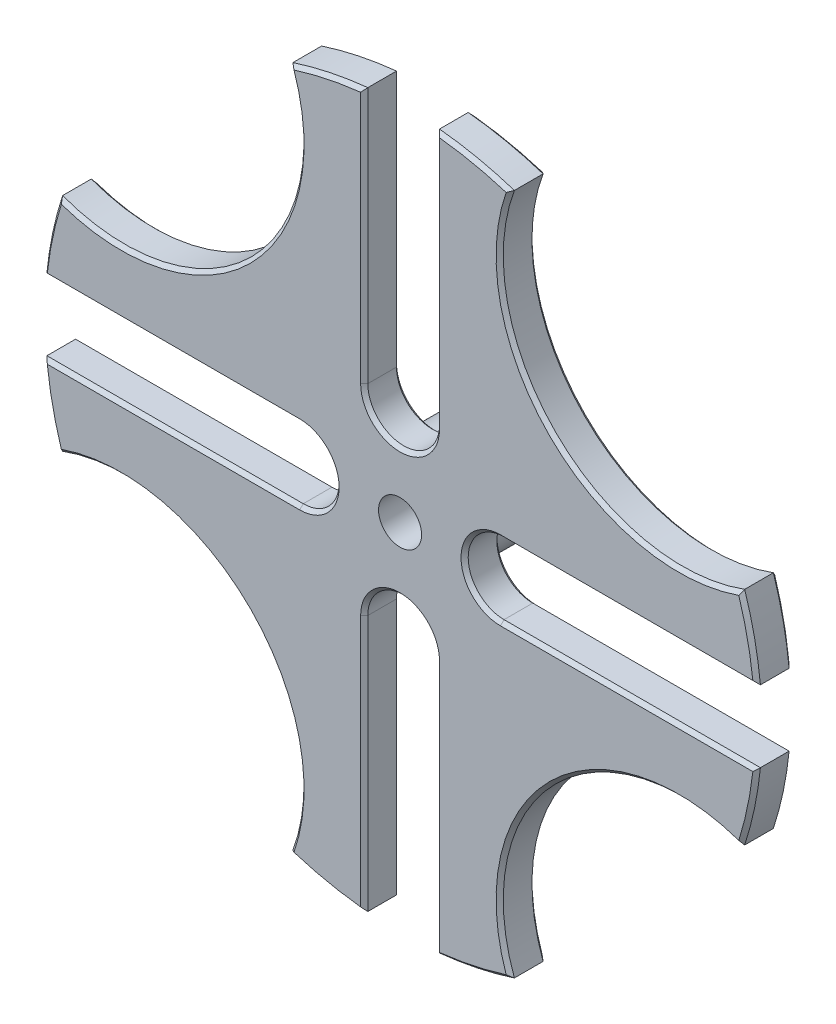
SolidWorks part; units mm, degrees
ref_plane "Ön Düzlem" through (0, 0, 0) normal (0, 0, 1) x (1, 0, 0)
ref_plane "Üst Düzlem" through (0, 0, 0) normal (0, 1, 0) x (1, 0, 0)
ref_plane "Sağ Düzlem" through (0, 0, 0) normal (1, 0, 0) x (0, 0, -1)
sketch "Sketch1" plane through (0, 0, 0) normal (0, 0, 1) x (1, 0, 0)
  circle A0 centre (0, 0) radius 50
  circle A1 centre (0, 0) radius 3
  dimension "D1" = 100
  dimension "D2" = 6
extrude "Boss-Extrude1" add sketch "Sketch1" along normal blind 5
sketch "Sketch2" plane through (0, 0, 5) normal (0, 0, 1) x (1, 0, 0)
  line L0 (0, 79.311) -> (0, -63.2271) construction
  line L1 (-72.315, 0) -> (65.8808, 0) construction
  line L2 (0, 14) -> (0, 86) construction
  line L3 (-5, 14) -> (-5, 86)
  line L4 (5, 14) -> (5, 86)
  line L5 (14, 0) -> (86, 0) construction
  line L6 (14, 5) -> (86, 5)
  line L7 (14, -5) -> (86, -5)
  line L8 (0, -14) -> (0, -86) construction
  line L9 (5, -14) -> (5, -86)
  line L10 (-5, -14) -> (-5, -86)
  line L11 (-14, 0) -> (-86, 0) construction
  line L12 (-14, -5) -> (-86, -5)
  line L13 (-14, 5) -> (-86, 5)
  line L14 (0, 0) -> (38.8909, 38.8909) construction
  arc A0 (-5, 14) -> (5, 14) centre (0, 14) ccw
  arc A1 (5, 86) -> (-5, 86) centre (0, 86) ccw
  circle A2 centre (0, 0) radius 50 construction
  arc A3 (14, 5) -> (14, -5) centre (14, 0) ccw
  arc A4 (86, -5) -> (86, 5) centre (86, 0) ccw
  arc A5 (5, -14) -> (-5, -14) centre (0, -14) ccw
  arc A6 (-5, -86) -> (5, -86) centre (0, -86) ccw
  arc A7 (-14, -5) -> (-14, 5) centre (-14, 0) ccw
  arc A8 (-86, 5) -> (-86, -5) centre (-86, 0) ccw
  circle A9 centre (38.8909, 38.8909) radius 25
  circle A10 centre (38.8909, -38.8909) radius 25
  circle A11 centre (-38.8909, -38.8909) radius 25
  circle A12 centre (-38.8909, 38.8909) radius 25
  point P7 (0, 50)
  point P19 (50, 0)
  point P26 (0, -50)
  point P33 (-50, 0)
  point P38 (0, 0)
  point P48 (0, 0)
  dimension "D1" = 5
  dimension "D6" = 50
  dimension "D2" = 72
  dimension "D4" = 45
  dimension "D5" = 55
  dimension "D3" = 4
  dimension "D7" = 4
extrude "Cut-Extrude1" cut sketch "Sketch2" against normal through all
chamfer "Chamfer1" distance 0.5 angle 45 50 edges at (3, 0, 0) (-21.2132, -21.2132, 0) (-10.279, -48.932, 0) (-5, -31.8747, 0) (0, -9, 0) (5, -31.8747, 0) (10.279, -48.932, 0) (21.2132, -21.2132, 0) (48.932, -10.279, 0) (31.8747, -5, 0) (9, 0, 0) (31.8747, 5, 0) (48.932, 10.279, 0) (21.2132, 21.2132, 0) (10.279, 48.932, 0) (5, 31.8747, 0) (0, 9, 0) (-5, 31.8747, 0) (-10.279, 48.932, 0) (-21.2132, 21.2132, 0) (-48.932, 10.279, 0) (-31.8747, 5, 0) (-9, 0, 0) (-31.8747, -5, 0) (-48.932, -10.279, 0) (3, 0, 5) (-9, 0, 5) (-31.8747, 5, 5) (-48.932, 10.279, 5) (-21.2132, 21.2132, 5) (-10.279, 48.932, 5) (-5, 31.8747, 5) (0, 9, 5) (5, 31.8747, 5) (10.279, 48.932, 5) (21.2132, 21.2132, 5) (48.932, 10.279, 5) (31.8747, 5, 5) (9, 0, 5) (31.8747, -5, 5) (48.932, -10.279, 5) (21.2132, -21.2132, 5) (10.279, -48.932, 5) (5, -31.8747, 5) (0, -9, 5) (-5, -31.8747, 5) (-10.279, -48.932, 5) (-21.2132, -21.2132, 5) (-48.932, -10.279, 5) (-31.8747, -5, 5)
sketch "Sketch4" plane through (0, 0, 0) normal (0, 0, -1) x (-1, 0, 0)
  circle A0 centre (0, 0) radius 3
  circle A1 centre (0, 0) radius 7.5
  arc A2 (5.5, -14) -> (-5.5, -14) centre (0, -14) ccw construction
  point P6 (0, -8.5)
  point P9 (0, -8.5)
  dimension "D1" = 6
  dimension "D2" = 15
extrude "Boss-Extrude3" add sketch "Sketch4" along normal blind 10 and the other way blind 5
chamfer "Chamfer2" distance 0.5 angle 45 2 edges at (-7.5, 0, -10) (-3, 0, -10)
